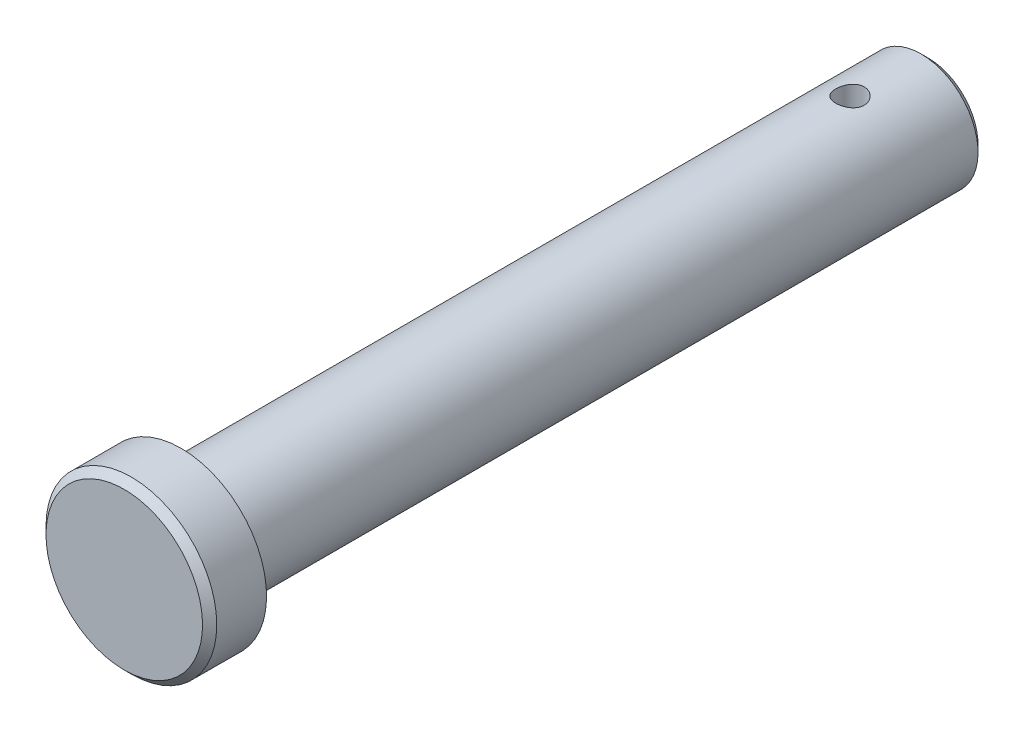
SolidWorks part; units mm, degrees
ref_plane "Front Plane" through (0, 0, 0) normal (0, 0, 1) x (1, 0, 0)
ref_plane "Top Plane" through (0, 0, 0) normal (0, 1, 0) x (1, 0, 0)
ref_plane "Right Plane" through (0, 0, 0) normal (1, 0, 0) x (0, 0, -1)
sketch "Sketch1" plane through (0, 0, 0) normal (1, 0, 0) x (0, 0, -1)
  line L0 (0, 0) -> (0, 12)
  line L1 (0, 12) -> (8, 12)
  line L2 (8, 12) -> (8, 8)
  line L3 (8, 8) -> (113, 8)
  line L4 (113, 8) -> (113, 0)
  line L5 (113, 0) -> (0, 0)
  dimension "D1" = 105
  dimension "D2" = 8
  dimension "D3" = 8
  dimension "D4" = 12
revolve "Revolve1" add sketch "Sketch1" angle 360 about L5
chamfer "Chamfer1" distance 1 angle 45 2 edges at (0, 8, -113) (0, 12, 0)
sketch "Sketch2" plane through (0, 0, 0) normal (0, 1, 0) x (1, 0, 0)
  line L0 (12, 8) -> (-12, 8) construction
  circle A0 centre (0, 102) radius 2
  point P4 (0, 0)
  dimension "D1" = 4
  dimension "D2" = 94
extrude "Cut-Extrude1" cut sketch "Sketch2" against normal through all both and the other way through all
